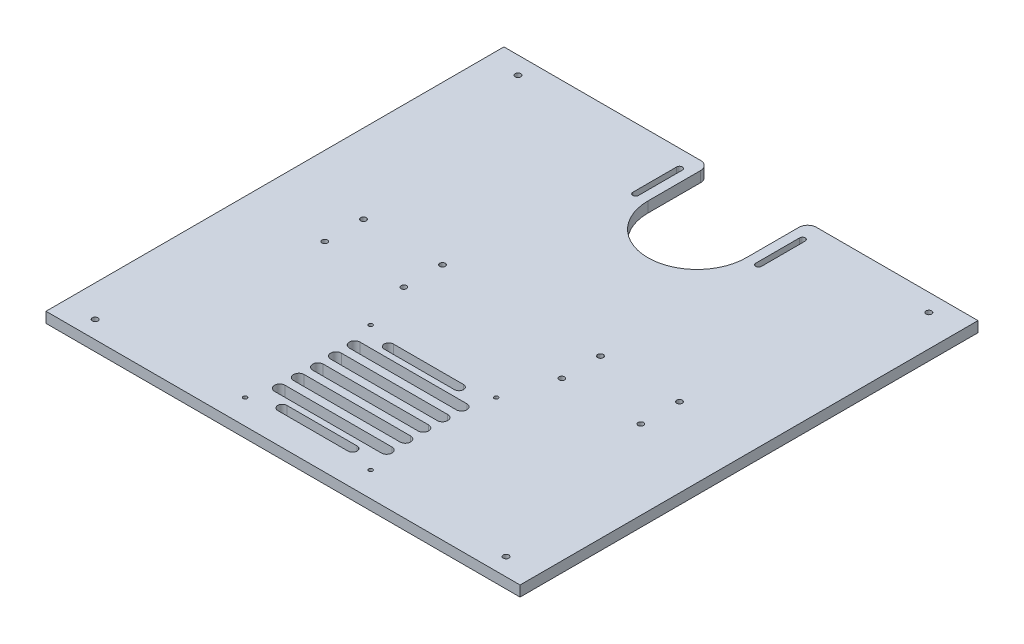
SolidWorks part; units mm, degrees
ref_plane "Front Plane" through (0, 0, 0) normal (0, 0, 1) x (1, 0, 0)
ref_plane "Top Plane" through (0, 0, 0) normal (0, 1, 0) x (1, 0, 0)
ref_plane "Right Plane" through (0, 0, 0) normal (1, 0, 0) x (0, 0, -1)
sketch "Sketch1" plane through (0, 0, 0) normal (0, 1, 0) x (1, 0, 0)
  line L0 (-145, 120) -> (125, 120)
  line L1 (-145, 120) -> (-145, -100.8)
  line L3 (125, 120) -> (125, -100.8)
  line L4 (0, 0) -> (0, 120) construction
  line L7 (-145, -100.8) -> (-145, -140.8)
  line L8 (-145, -140.8) -> (125, -140.8)
  line L9 (125, -100.8) -> (125, -140.8)
  circle A0 centre (-100, -5) radius 1.6
  circle A2 centre (80, -5) radius 1.6
  circle A3 centre (-55, -5) radius 1.6
  circle A4 centre (35, -5) radius 1.6
  circle A6 centre (-55, -5) radius 1.125 construction
  dimension "D1" = 3.2
  dimension "D2" = 40
extrude "Boss-Extrude1" add sketch "Sketch1" along normal blind 6
sketch "Sketch3" plane through (0, 6, 0) normal (0, 1, 0) x (1, 0, 0)
  line L3 (0, 120) -> (0, 0) construction
  line L4 (125, 120) -> (-145, 120) construction
  line L5 (-28, 85) -> (-28, 120)
  line L60 (28, 85) -> (28, 120)
  line L61 (28, 120) -> (-28, 120)
  arc A0 (-28, 85) -> (28, 85) centre (0, 85) ccw
  dimension "D1" = 28
  dimension "D2" = 35
extrude "Cut-Extrude1" cut sketch "Sketch3" against normal through all both and the other way through all
sketch "Sketch4" plane through (0, 0, 0) normal (0, -1, 0) x (1, 0, 0)
  circle A0 centre (107, -110) radius 1.6
  circle A1 centre (-127, -110) radius 1.6
  circle A2 centre (107, 130.8) radius 1.6
  circle A3 centre (-127, 130.8) radius 1.6
extrude "Cut-Extrude2" cut sketch "Sketch4" against normal blind 10
sketch "Sketch5" plane through (0, 6, 0) normal (0, 1, 0) x (1, 0, 0)
  line L0 (28, 85) -> (28, 120) construction
  line L1 (-28, 120) -> (-28, 85) construction
  line L2 (28, 85) -> (28, 120) construction
  line L3 (-28, 120) -> (-28, 85) construction
  line L4 (-28, 120) -> (28, 120) construction
  line L5 (-35, 120) -> (-35, 85) construction
  line L6 (-28, 120) -> (-145, 120) construction
  line L7 (-35, 110) -> (-35, 85) construction
  line L8 (-33.4, 110) -> (-33.4, 85)
  line L9 (-36.6, 110) -> (-36.6, 85)
  line L10 (0, 120) -> (0, 85) construction
  line L11 (35, 120) -> (35, 85) construction
  line L12 (35, 110) -> (35, 85) construction
  line L13 (33.4, 110) -> (33.4, 85)
  line L14 (36.6, 110) -> (36.6, 85)
  arc A0 (-33.4, 110) -> (-36.6, 110) centre (-35, 110) ccw
  arc A1 (-36.6, 85) -> (-33.4, 85) centre (-35, 85) ccw
  arc A2 (33.4, 110) -> (36.6, 110) centre (35, 110) cw
  arc A3 (36.6, 85) -> (33.4, 85) centre (35, 85) cw
  point P8 (-35, 110)
  point P12 (-35, 97.5)
  point P21 (35, 97.5)
  dimension "D3" = 1.6
  dimension "D2" = 10
extrude "Cut-Extrude3" cut sketch "Sketch5" against normal blind 10
fillet "Fillet1" radius 5 2 edges at (28, 3, -120) (-28, 3, -120)
sketch "Sketch6" plane through (0, 6, 0) normal (0, 1, 0) x (1, 0, 0)
  line L0 (-10, -140.8) -> (-10, -40.9987) construction
  line L1 (-145, -140.8) -> (125, -140.8) construction
  line L2 (-40, -90.8994) -> (20, -90.8994) construction
  line L3 (-45.75, -55.1494) -> (25.75, -55.1494) construction
  line L4 (-45.75, -55.1494) -> (-45.75, -126.6494) construction
  line L5 (-45.75, -126.6494) -> (25.75, -126.6494) construction
  line L6 (25.75, -55.1494) -> (25.75, -126.6494) construction
  line L7 (-45.75, -55.1494) -> (25.75, -126.6494) construction
  line L8 (-45.75, -126.6494) -> (25.75, -55.1494) construction
  line L9 (-40, -87.8994) -> (20, -87.8994)
  line L10 (-40, -93.8994) -> (20, -93.8994)
  line L11 (-40.3168, -80.3259) -> (20.3168, -80.3259) construction
  line L12 (-40.3168, -77.3259) -> (20.3168, -77.3259)
  line L13 (-40.3168, -83.3259) -> (20.3168, -83.3259)
  line L14 (-40.436, -69.5711) -> (20.436, -69.5711) construction
  line L15 (-40.436, -66.5711) -> (20.436, -66.5711)
  line L16 (-40.436, -72.5711) -> (20.436, -72.5711)
  line L17 (-30, -60.5923) -> (10, -60.5923) construction
  line L18 (-30, -58.0215) -> (10, -58.0215)
  line L19 (-30, -63.1632) -> (10, -63.1632)
  line L20 (-74.1524, -90.8994) -> (67.5301, -90.8994) construction
  line L21 (-45.75, -126.6494) -> (25.75, -126.6494) construction
  line L22 (-30, -121.2064) -> (10, -121.2064) construction
  line L23 (-30, -123.7773) -> (10, -123.7773)
  line L24 (-30, -118.6356) -> (10, -118.6356)
  line L25 (-40.436, -112.2277) -> (20.436, -112.2277) construction
  line L26 (-40.436, -115.2277) -> (20.436, -115.2277)
  line L27 (-40.436, -109.2277) -> (20.436, -109.2277)
  line L28 (-40.3168, -101.4728) -> (20.3168, -101.4728) construction
  line L29 (-40.3168, -104.4728) -> (20.3168, -104.4728)
  line L30 (-40.3168, -98.4728) -> (20.3168, -98.4728)
  circle A0 centre (25.75, -55.1494) radius 1.125
  circle A1 centre (-45.75, -55.1494) radius 1.125
  circle A2 centre (-45.75, -126.6494) radius 1.125
  circle A3 centre (25.75, -126.6494) radius 1.125
  arc A4 (-40, -87.8994) -> (-40, -93.8994) centre (-40, -90.8994) ccw
  arc A5 (20, -93.8994) -> (20, -87.8994) centre (20, -90.8994) ccw
  arc A6 (-40.3168, -77.3259) -> (-40.3168, -83.3259) centre (-40.3168, -80.3259) ccw
  arc A7 (20.3168, -83.3259) -> (20.3168, -77.3259) centre (20.3168, -80.3259) ccw
  arc A8 (-40.436, -66.5711) -> (-40.436, -72.5711) centre (-40.436, -69.5711) ccw
  arc A9 (20.436, -72.5711) -> (20.436, -66.5711) centre (20.436, -69.5711) ccw
  arc A10 (-30, -58.0215) -> (-30, -63.1632) centre (-30, -60.5923) ccw
  arc A11 (10, -63.1632) -> (10, -58.0215) centre (10, -60.5923) ccw
  arc A12 (-30, -123.7773) -> (-30, -118.6356) centre (-30, -121.2064) cw
  arc A13 (10, -118.6356) -> (10, -123.7773) centre (10, -121.2064) cw
  arc A14 (-40.436, -115.2277) -> (-40.436, -109.2277) centre (-40.436, -112.2277) cw
  arc A15 (20.436, -109.2277) -> (20.436, -115.2277) centre (20.436, -112.2277) cw
  arc A16 (-40.3168, -104.4728) -> (-40.3168, -98.4728) centre (-40.3168, -101.4728) cw
  arc A17 (20.3168, -98.4728) -> (20.3168, -104.4728) centre (20.3168, -101.4728) cw
  point P4 (-10, -80.3259)
  point P6 (-10, -90.8994)
  point P16 (-10, -90.8994)
  point P23 (-10, -80.3259)
  point P28 (-10, -69.5711)
  point P31 (-10, -69.5711)
  point P36 (-10, -60.5923)
  point P47 (-10, -121.2064)
  point P54 (-10, -112.2277)
  point P61 (-10, -101.4728)
  dimension "D3" = 2.25
  dimension "D4" = 2.25
  dimension "D5" = 2.25
  dimension "D6" = 2.25
  dimension "D8" = 3
  dimension "D9" = 3
  dimension "D10" = 3
  dimension "D1" = 71.5
  dimension "D2" = 71.5
  dimension "D7" = 60
  dimension "D11" = 40
extrude "Cut-Extrude4" cut sketch "Sketch6" against normal blind 10
sketch "Sketch7" plane through (0, 6, 0) normal (0, 1, 0) x (1, 0, 0)
  circle A0 centre (-100, -27) radius 1.55
  circle A1 centre (-55, -27) radius 1.55
  circle A2 centre (35, -27) radius 1.55
  circle A3 centre (80, -27) radius 1.55
  dimension "D1" = 3.1
extrude "Cut-Extrude5" cut sketch "Sketch7" against normal blind 10
